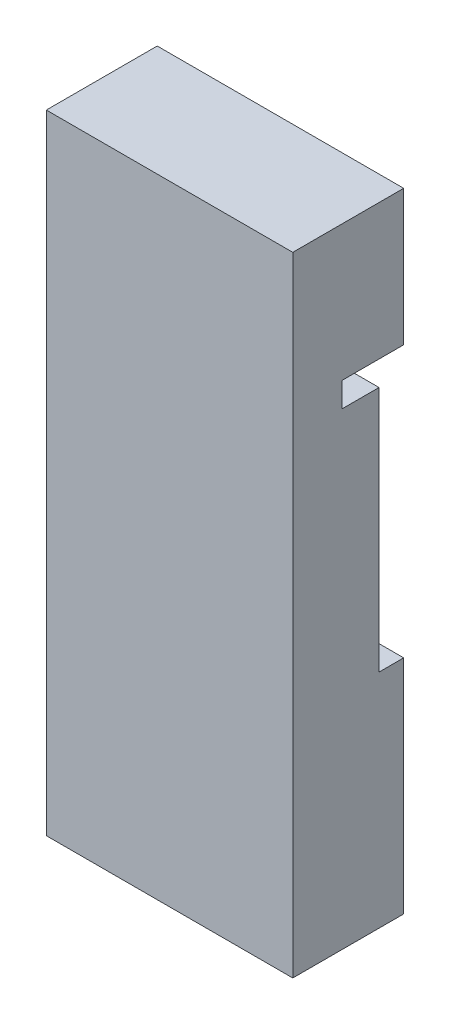
SolidWorks part; units mm, degrees
ref_plane "Plan de face" through (0, 0, 0) normal (0, 0, 1) x (1, 0, 0)
ref_plane "Plan de dessus" through (0, 0, 0) normal (0, 1, 0) x (1, 0, 0)
ref_plane "Plan de droite" through (0, 0, 0) normal (1, 0, 0) x (0, 0, -1)
sketch "Esquisse1" plane through (0, 0, 0) normal (0, 0, 1) x (1, 0, 0)
  line L1 (-15.9031, 5.0885) -> (4.0969, 5.0885)
  line L2 (-15.9031, 5.0885) -> (-15.9031, -45.9115)
  line L3 (-15.9031, -45.9115) -> (4.0969, -45.9115)
  line L4 (4.0969, 5.0885) -> (4.0969, -45.9115)
  dimension "D1" = 51
  dimension "D2" = 20
extrude "Extrusion1" add sketch "Esquisse1" along normal blind 9
sketch "Esquisse3" plane through (0, 0, 0) normal (0, 0, -1) x (-1, 0, 0)
  line L0 (-4.0969, -45.9115) -> (-4.0969, 5.0885) construction
  line L1 (2.9031, -7.9115) -> (-4.0969, -7.9115)
  line L2 (2.9031, -7.9115) -> (2.9031, -27.9115)
  line L3 (2.9031, -27.9115) -> (-4.0969, -27.9115)
  line L4 (-4.0969, -7.9115) -> (-4.0969, -27.9115)
  line L5 (-4.0969, -27.9115) -> (2.9031, -27.9115) construction
extrude "Enlèv. mat.-Extru.1" cut sketch "Esquisse3" against normal blind 2
sketch "Esquisse4" plane through (4.0969, 0, 0) normal (1, 0, 0) x (0, 0, -1)
  line L1 (-5, -5.9115) -> (0, -5.9115)
  line L2 (-5, -5.9115) -> (-5, -7.9115)
  line L3 (-5, -7.9115) -> (0, -7.9115)
  line L4 (0, -5.9115) -> (0, -7.9115)
extrude "Enlèv. mat.-Extru.2" cut sketch "Esquisse4" against normal up to next
